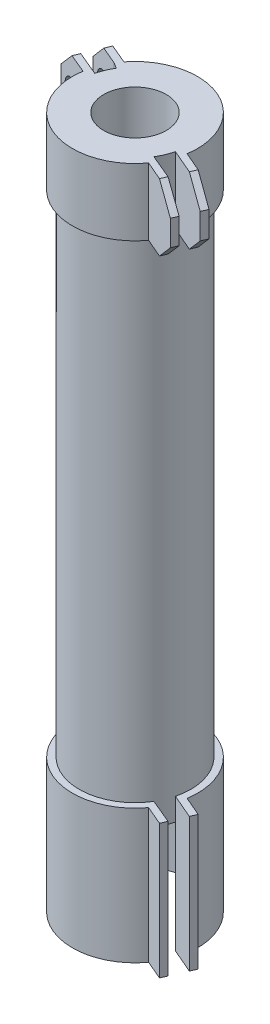
SolidWorks part; units mm, degrees
ref_plane "Front Plane" through (0, 0, 0) normal (0, 0, 1) x (1, 0, 0)
ref_plane "Top Plane" through (0, 0, 0) normal (0, 1, 0) x (1, 0, 0)
ref_plane "Right Plane" through (0, 0, 0) normal (1, 0, 0) x (0, 0, -1)
sketch "Sketch1" plane through (0, 0, 0) normal (0, 1, 0) x (1, 0, 0)
  circle A0 centre (0, 0) radius 14
  circle A1 centre (0, 0) radius 25
extrude "Boss-Extrude1" add sketch "Sketch1" along normal blind 150 and the other way blind 110
sketch "Sketch2" plane through (0, 150, 0) normal (0, 1, 0) x (1, 0, 0)
  line L0 (-23.9158, 14.5613) -> (-21.3534, 13.0012)
  line L1 (27.6629, -4.3318) -> (39.4621, -9.4007) construction
  line L2 (44.868, -11.7231) -> (43.6838, -14.4795) construction
  line L3 (43.6838, -14.4795) -> (24.2379, -6.1256) construction
  line L4 (2455.3742, -1050.5441) -> (780.405, -330.9757) construction
  line L5 (2461.7131, -1035.4958) -> (780.405, -330.9757) construction
  line L6 (24.2379, -6.1256) -> (43.6838, -14.4795)
  line L7 (43.6838, -14.4795) -> (44.868, -11.7231)
  line L8 (44.868, -11.7231) -> (27.6629, -4.3318)
  line L9 (39.4621, -9.4007) -> (24.8065, -3.1047) construction
  line L10 (-22.1243, 17.1614) -> (-39.2242, 24.4029)
  line L11 (-39.2242, 24.4029) -> (-40.4083, 21.6465)
  line L12 (-40.4083, 21.6465) -> (-23.9158, 14.5613)
  line L13 (-24.2221, 6.188) -> (-43.5009, 14.2664) construction
  line L14 (-43.5009, 14.2664) -> (-24.2221, 6.188)
  line L15 (-43.5009, 14.2664) -> (-44.6603, 11.4995)
  line L16 (-44.6603, 11.4995) -> (-27.6562, 4.3742)
  line L17 (40.8488, -21.0787) -> (21.3977, -12.9282) construction
  line L18 (21.3977, -12.9282) -> (40.8488, -21.0787)
  line L19 (40.8488, -21.0787) -> (39.6646, -23.8352)
  line L20 (39.6646, -23.8352) -> (22.6143, -16.5103)
  line L21 (40.8488, -21.0787) -> (39.6646, -23.8352) construction
  line L22 (-21.1284, 13.3638) -> (-40.4083, 21.6465) construction
  line L23 (-19.3286, 15.8558) -> (-39.2242, 24.4029) construction
  arc A0 (24.2379, -6.1256) -> (-21.3534, 13.0012) centre (0, 0) ccw
  circle A1 centre (0, 0) radius 25 construction
  arc A2 (27.6629, -4.3318) -> (-22.1243, 17.1614) centre (0, 0) ccw
  arc A3 (-24.2221, 6.188) -> (21.3977, -12.9282) centre (0, 0) ccw
  arc A4 (-27.6562, 4.3742) -> (22.6143, -16.5103) centre (0, 0) ccw
  arc A5 (27.1465, -6.8606) -> (-23.9158, 14.5613) centre (0, 0) ccw construction
  arc A6 (-27.1287, 6.9305) -> (23.9655, -14.4795) centre (0, 0) ccw construction
  dimension "D1" = 3
  dimension "D2" = 3
extrude "Boss-Extrude2" add sketch "Sketch2" against normal blind 30
sketch "Sketch4" plane through (2.798, 0, -6.6072) normal (0.39, 0, -0.9208) x (-0.9208, 0, -0.39)
  line L0 (45.635, 120) -> (45.635, 150) construction
  line L1 (27.065, 150) -> (45.635, 150) construction
  circle A96 centre (36.35, 135) radius 6
  dimension "D1" = 12
  dimension "D2" = 9.285
  dimension "D3" = 15
extrude "Cut-Extrude1" cut sketch "Sketch4" against normal blind 30
sketch "Sketch5" plane through (0, -110, 0) normal (0, -1, 0) x (1, 0, 0)
  line L0 (-21.3534, -13.0012) -> (-23.9158, -14.5613) construction
  line L1 (-23.9158, -14.5613) -> (-40.4083, -21.6465) construction
  line L2 (-40.4083, -21.6465) -> (-39.2242, -24.4029) construction
  line L3 (-39.2242, -24.4029) -> (-22.1243, -17.1614) construction
  line L4 (27.6629, 4.3318) -> (44.868, 11.7231) construction
  line L5 (44.868, 11.7231) -> (43.6838, 14.4795) construction
  line L6 (43.6838, 14.4795) -> (24.2379, 6.1256) construction
  line L7 (21.3977, 12.9282) -> (40.8488, 21.0787) construction
  line L8 (40.8488, 21.0787) -> (39.6646, 23.8352) construction
  line L9 (39.6646, 23.8352) -> (22.6143, 16.5103) construction
  line L10 (-27.6562, -4.3742) -> (-44.6603, -11.4995) construction
  line L11 (-44.6603, -11.4995) -> (-43.5009, -14.2664) construction
  line L12 (-43.5009, -14.2664) -> (-24.2221, -6.188) construction
  line L13 (-21.3534, -13.0012) -> (-23.9158, -14.5613)
  line L14 (-23.9158, -14.5613) -> (-40.4083, -21.6465)
  line L15 (-40.4083, -21.6465) -> (-39.2242, -24.4029)
  line L16 (-39.2242, -24.4029) -> (-22.1243, -17.1614)
  line L17 (27.6629, 4.3318) -> (44.868, 11.7231)
  line L18 (44.868, 11.7231) -> (43.6838, 14.4795)
  line L19 (43.6838, 14.4795) -> (24.2379, 6.1256)
  line L20 (21.3977, 12.9282) -> (40.8488, 21.0787)
  line L21 (40.8488, 21.0787) -> (39.6646, 23.8352)
  line L22 (39.6646, 23.8352) -> (22.6143, 16.5103)
  line L23 (-27.6562, -4.3742) -> (-44.6603, -11.4995)
  line L24 (-44.6603, -11.4995) -> (-43.5009, -14.2664)
  line L25 (-43.5009, -14.2664) -> (-24.2221, -6.188)
  arc A0 (-21.3534, -13.0012) -> (24.2379, 6.1256) centre (0, 0) ccw construction
  arc A1 (-22.1243, -17.1614) -> (27.6629, 4.3318) centre (0, 0) ccw construction
  arc A2 (21.3977, 12.9282) -> (-24.2221, -6.188) centre (0, 0) ccw construction
  arc A3 (22.6143, 16.5103) -> (-27.6562, -4.3742) centre (0, 0) ccw construction
  arc A4 (-21.3534, -13.0012) -> (24.2379, 6.1256) centre (0, 0) ccw
  arc A5 (-22.1243, -17.1614) -> (27.6629, 4.3318) centre (0, 0) ccw
  arc A6 (21.3977, 12.9282) -> (-24.2221, -6.188) centre (0, 0) ccw
  arc A7 (22.6143, 16.5103) -> (-27.6562, -4.3742) centre (0, 0) ccw
sketch "Sketch6" plane through (-2.4644, 0, 5.7365) normal (-0.3947, 0, 0.9188) x (0.9188, 0, 0.3947)
  line L0 (36.5736, 150) -> (45.8521, 140.7215)
  line L1 (27.295, 150) -> (45.8521, 150) construction
  line L2 (45.8521, 140.7215) -> (66.0714, 154.8459)
  line L3 (66.0714, 154.8459) -> (36.5736, 150)
  line L4 (36.5736, 120) -> (62.8746, 146.301)
  line L5 (27.295, 120) -> (45.8521, 120) construction
  line L6 (62.8746, 146.301) -> (73.1322, 136.0435)
  line L7 (73.1322, 136.0435) -> (73.1322, 101.7126)
  line L8 (73.1322, 101.7126) -> (36.5736, 120)
extrude "Cut-Extrude3" cut sketch "Sketch6" against normal blind 30
sketch "Sketch7" plane through (-2.5716, 0, 6.137) normal (-0.3865, 0, 0.9223) x (0.9223, 0, 0.3865)
  line L0 (-36.4162, 150) -> (-45.6344, 140.7817)
  line L1 (-45.6344, 150) -> (-27.1979, 150) construction
  line L2 (-45.6344, 140.7817) -> (-52.2388, 153.9827)
  line L3 (-52.2388, 153.9827) -> (-36.4162, 153.9827)
  line L4 (-36.4162, 153.9827) -> (-36.4162, 150)
  line L5 (-36.4162, 120) -> (-66.0894, 149.6732)
  line L6 (-45.6344, 120) -> (-27.1979, 120) construction
  line L7 (-66.0894, 149.6732) -> (-66.0894, 112.1362)
  line L8 (-66.0894, 112.1362) -> (-36.4162, 120)
extrude "Cut-Extrude4" cut sketch "Sketch7" against normal blind 30
sketch "Sketch8" plane through (0, -110, 0) normal (0, -1, 0) x (1, 0, 0)
  line L1 (-23.9158, -14.5613) -> (-31.9382, -18.0078) construction
  line L13 (-30.7604, -20.8187) -> (-22.1243, -17.1614) construction
  line L14 (27.6629, 4.3318) -> (36.3428, 8.0607) construction
  line L15 (36.3428, 8.0607) -> (35.1587, 10.8171) construction
  line L16 (35.1587, 10.8171) -> (24.2379, 6.1256) construction
  line L17 (-21.3534, -13.0012) -> (-23.9158, -14.5613) construction
  line L18 (-27.6562, -4.3742) -> (-36.1582, -7.9368) construction
  line L20 (-34.9988, -10.7037) -> (-24.2221, -6.188) construction
  line L21 (21.3977, 12.9282) -> (32.2908, 17.4927) construction
  line L22 (32.2908, 17.4927) -> (31.1395, 20.1727) construction
  line L23 (31.1395, 20.1727) -> (22.6143, 16.5103) construction
  line L24 (-23.9158, -14.5613) -> (-31.9382, -18.0078)
  line L26 (-30.7604, -20.8187) -> (-22.1243, -17.1614)
  line L27 (27.6629, 4.3318) -> (36.3428, 8.0607)
  line L28 (36.3428, 8.0607) -> (35.1587, 10.8171)
  line L29 (35.1587, 10.8171) -> (24.2379, 6.1256)
  line L30 (-21.3534, -13.0012) -> (-23.9158, -14.5613)
  line L31 (-27.6562, -4.3742) -> (-36.1582, -7.9368)
  line L33 (-34.9988, -10.7037) -> (-24.2221, -6.188)
  line L34 (21.3977, 12.9282) -> (32.2908, 17.4927)
  line L35 (32.2908, 17.4927) -> (31.1395, 20.1727)
  line L36 (31.1395, 20.1727) -> (22.6143, 16.5103)
  line L37 (-44.6603, -11.4995) -> (-43.5009, -14.2664) construction
  line L38 (-43.5009, -14.2664) -> (-34.9988, -10.7037) construction
  line L40 (-36.1582, -7.9368) -> (-44.6603, -11.4995) construction
  line L41 (-31.9382, -18.0078) -> (-40.4083, -21.6465) construction
  line L42 (-40.4083, -21.6465) -> (-39.2242, -24.4029) construction
  line L43 (-39.2242, -24.4029) -> (-30.7604, -20.8187) construction
  line L45 (-44.6603, -11.4995) -> (-43.5009, -14.2664)
  line L46 (-43.5009, -14.2664) -> (-34.9988, -10.7037)
  line L48 (-36.1582, -7.9368) -> (-44.6603, -11.4995)
  line L49 (-31.9382, -18.0078) -> (-40.4083, -21.6465)
  line L50 (-40.4083, -21.6465) -> (-39.2242, -24.4029)
  line L51 (-39.2242, -24.4029) -> (-30.7604, -20.8187)
  arc A4 (-22.1243, -17.1614) -> (27.6629, 4.3318) centre (0, 0) ccw construction
  arc A5 (-21.3534, -13.0012) -> (24.2379, 6.1256) centre (0, 0) ccw construction
  arc A6 (21.3977, 12.9282) -> (-24.2221, -6.188) centre (0, 0) ccw construction
  arc A7 (22.6143, 16.5103) -> (-27.6562, -4.3742) centre (0, 0) ccw construction
  arc A8 (-22.1243, -17.1614) -> (27.6629, 4.3318) centre (0, 0) ccw
  arc A9 (-21.3534, -13.0012) -> (24.2379, 6.1256) centre (0, 0) ccw
  arc A10 (21.3977, 12.9282) -> (-24.2221, -6.188) centre (0, 0) ccw
  arc A11 (22.6143, 16.5103) -> (-27.6562, -4.3742) centre (0, 0) ccw
extrude "Boss-Extrude3" add sketch "Sketch8" against normal blind 10 and the other way blind 50
sketch "Sketch10" plane through (2.798, 0, -6.6072) normal (0.39, 0, -0.9208) x (-0.9208, 0, -0.39)
  circle A0 centre (35.5157, -149.9157) radius 6
extrude "Cut-Extrude5" cut sketch "Sketch10" against normal blind 20
